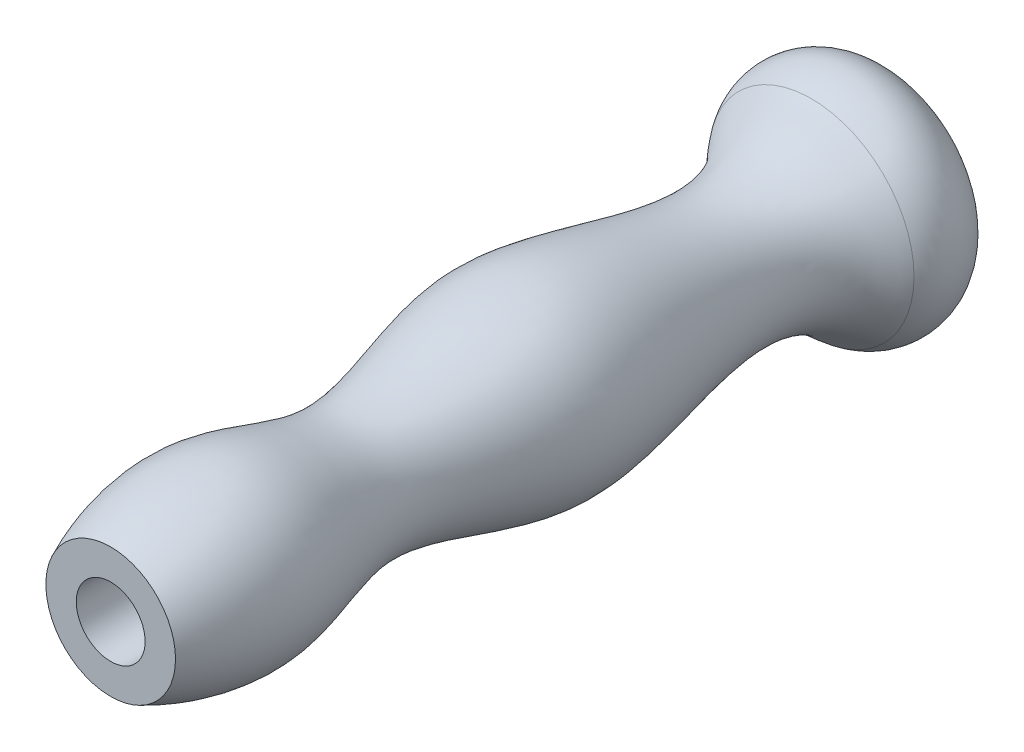
SolidWorks part; units mm, degrees
material "Roble"
ref_plane "Alzado" through (0, 0, 0) normal (0, 0, 1) x (1, 0, 0)
ref_plane "Planta" through (0, 0, 0) normal (0, 1, 0) x (1, 0, 0)
ref_plane "Vista lateral" through (0, 0, 0) normal (1, 0, 0) x (0, 0, -1)
sketch "Croquis1" plane through (0, 0, 0) normal (1, 0, 0) x (0, 0, -1)
  line L0 (-65.0812, 0) -> (72.2748, 0) construction
  line L1 (55, 0) -> (-55, 0) construction
  line L2 (-55.7047, 0) -> (-55.7047, 8)
  line L3 (41.2953, 0) -> (41.2953, 7.3092)
  line L4 (-55.7047, 0) -> (41.2953, 0)
  arc A0 (41.2953, 7.3092) -> (30.7701, 12.6856) centre (34.6595, 7.3092) ccw
  spline S0 degree 3 poles (-55.7047, 8) (-51.1837, 10.0681) (-44.6832, 11.548) (-35.2801, 9.7899) (-23.7356, 5.1221) (-2.8292, 17.768) (20.9641, 2.745) (29.9114, 12.0644) (30.7701, 12.6856) knots 0 0 0 0 0.161961 0.202044 0.307706 0.544762 0.91235 0.946499 0.946499 0.946499 0.946499
  dimension "D2" = 6.6357
  dimension "D1" = 97
  dimension "D4" = 8
revolve "Revolución1" add sketch "Croquis1" angle 360 about L0
sketch "Croquis2" plane through (0, 0, 55.7047) normal (0, 0, 1) x (1, 0, 0)
  circle A0 centre (0, 0) radius 4.25
  dimension "D1" = 8.5
extrude "Cortar-Extruir1" cut sketch "Croquis2" against normal blind 121
